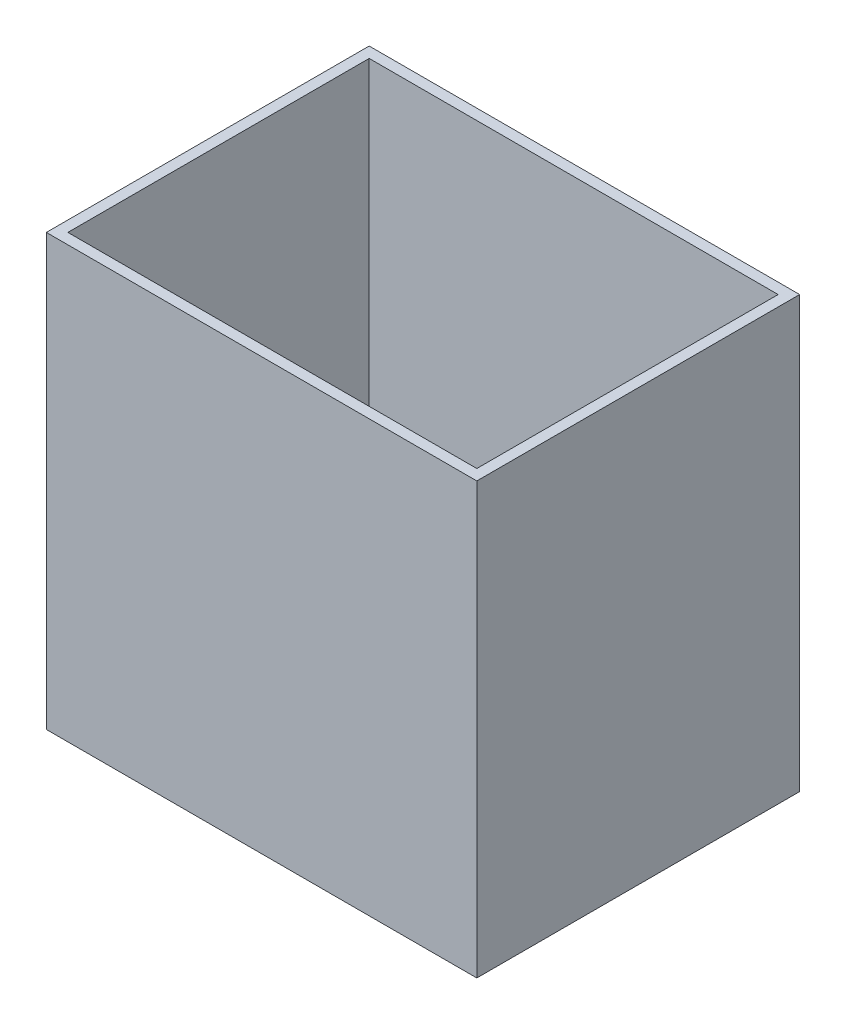
SolidWorks part; units mm, degrees
ref_plane "前视基准面" through (0, 0, 0) normal (0, 0, 1) x (1, 0, 0)
ref_plane "上视基准面" through (0, 0, 0) normal (0, 1, 0) x (1, 0, 0)
ref_plane "右视基准面" through (0, 0, 0) normal (1, 0, 0) x (0, 0, -1)
other "Configuration Table"
sketch "草图1" plane through (0, 0, 0) normal (0, 1, 0) x (1, 0, 0)
  line L1 (0, 0) -> (80, 0)
  line L2 (0, 0) -> (0, 60)
  line L3 (0, 60) -> (80, 60)
  line L4 (80, 0) -> (80, 60)
  dimension "D1" = 80
  dimension "D2" = 60
extrude "凸台-拉伸1" add sketch "草图1" along normal blind 80
shell "抽壳1" thickness 2
